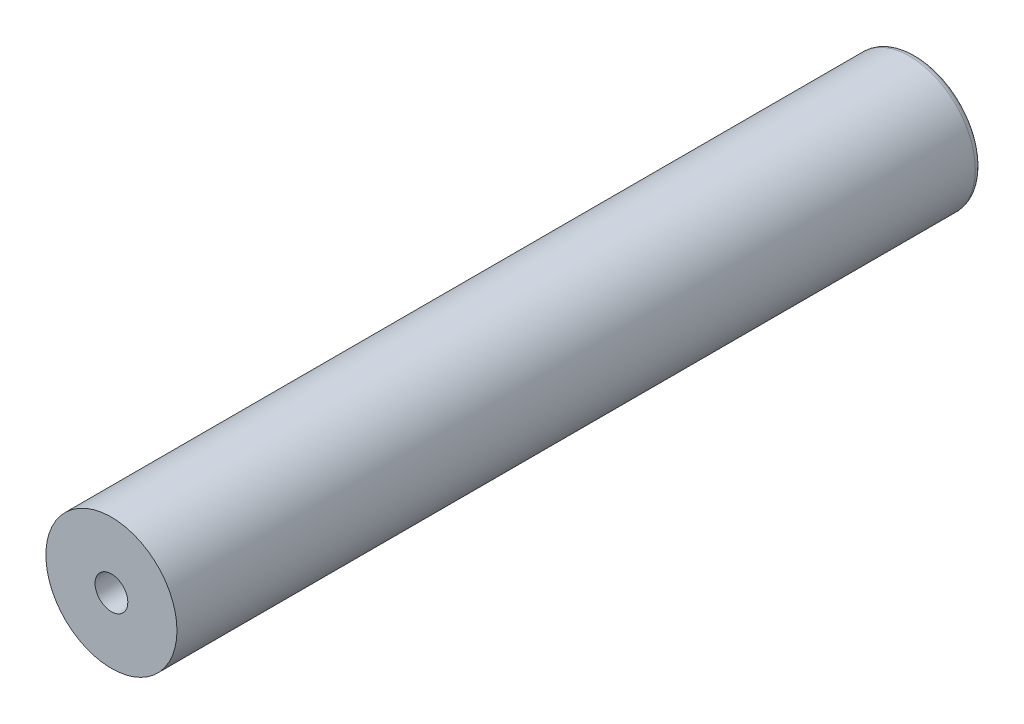
SolidWorks part; units mm, degrees
ref_plane "Plano frontal" through (0, 0, 0) normal (0, 0, 1) x (1, 0, 0)
ref_plane "Plano superior" through (0, 0, 0) normal (0, 1, 0) x (1, 0, 0)
ref_plane "Plano direito" through (0, 0, 0) normal (1, 0, 0) x (0, 0, -1)
sketch "Esboço1" plane through (0, 0, 0) normal (0, 0, 1) x (1, 0, 0)
  circle A0 centre (240.7084, 2.5961) radius 5
  dimension "D1" = 10
extrude "Ressalto-extrusão1" add sketch "Esboço1" along normal blind 61.4
hole_wizard "Furo roscado de M3x0.52" positions "Esboço5" profile "Esboço4" tap size "M3x0.5" standard "Métrico Ansi"
sketch "Esboço5" plane through (0, 0, 0) normal (0, 0, -1) x (-1, 0, 0)
  point P0 (-240.7084, 2.5961)
sketch "Esboço4" plane through (240.7084, 2.5961, 0) normal (1, 0, 0) x (0, 1, 0)
  line L0 (0, 0) -> (0, 9.2511)
  line L1 (0, 9.2511) -> (1.25, 8.5)
  line L2 (1.25, 8.5) -> (1.25, 0)
  line L5 (1.25, 0) -> (0, 0)
  line L10 (0, 9.2511) -> (-1.25, 8.5) construction
  line L11 (0, -6.35) -> (0, 107.95) construction
  dimension "Tap Drill Dia." = 2.5
  dimension "Tap Drill Depth" = 8.5
  dimension "Drill Angle" = 118
cosmetic thread "Rosca de furo2" parameters "D1"=6, "D2"=3
cosmetic thread "Representação de rosca1" parameters "D1"=6, "D2"=3
fillet "Filete1" radius 0.5 1 edges at (245.7084, 2.5961, 0)
hole_wizard "Broca de rosquear para tarraxa de M3x0.51" positions "Esboço7" profile "Esboço6" hole size "M3x0.5" standard "Métrico Ansi"
sketch "Esboço7" plane through (0, 0, 61.4) normal (0, 0, 1) x (1, 0, 0)
  circle A0 centre (240.7084, 2.5961) radius 5 construction
  point P0 (240.7084, 2.5961)
  dimension "D1" = 0
sketch "Esboço6" plane through (240.7084, 2.5961, 61.4) normal (1, 0, 0) x (0, -1, 0)
  line L0 (0, 0) -> (0, 5.7511)
  line L1 (0, 5.7511) -> (1.25, 5)
  line L2 (1.25, 5) -> (1.25, 0)
  line L5 (1.25, 0) -> (0, 0)
  line L10 (0, 5.7511) -> (-1.25, 5) construction
  line L11 (0, -6.35) -> (0, 107.95) construction
  dimension "Hole Dia." = 2.5
  dimension "Hole Depth" = 5
  dimension "Drill Angle" = 118
